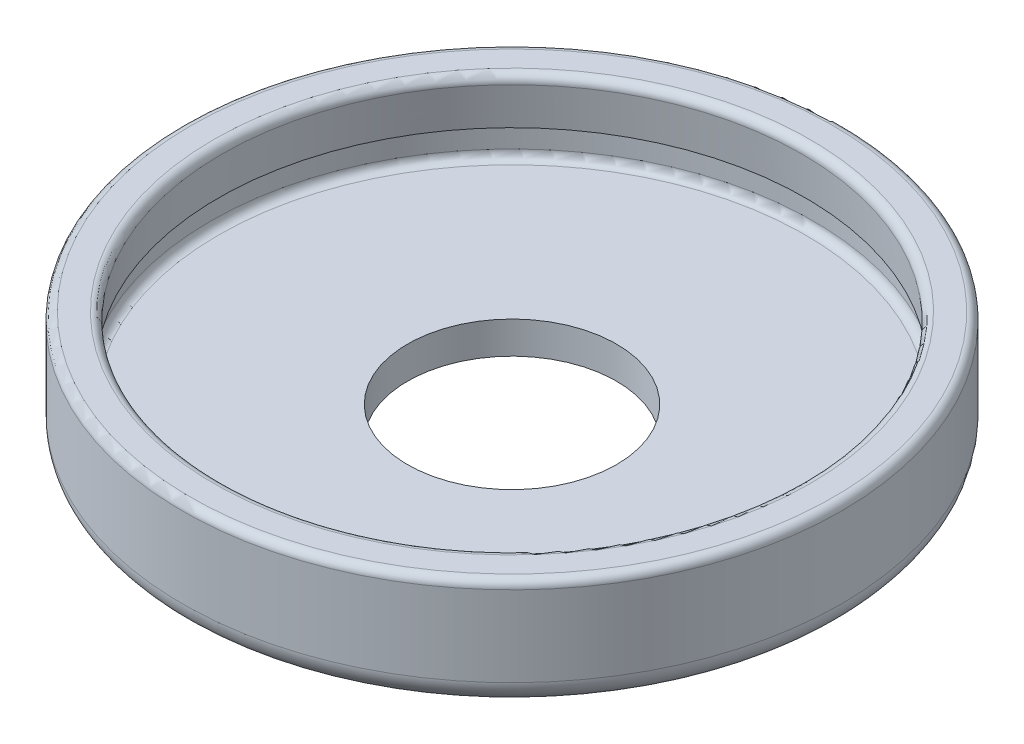
SolidWorks part; units mm, degrees
ref_plane "Front Plane" through (0, 0, 0) normal (0, 0, 1) x (1, 0, 0)
ref_plane "Top Plane" through (0, 0, 0) normal (0, 1, 0) x (1, 0, 0)
ref_plane "Right Plane" through (0, 0, 0) normal (1, 0, 0) x (0, 0, -1)
sketch "Sketch1" plane through (0, 0, 0) normal (0, 0, 1) x (1, 0, 0)
  line L0 (-1.5505, 0) -> (75.9722, 0) construction
  line L1 (0, -1.5505) -> (0, 75.9722) construction
  line L2 (5.207, 1.778) -> (5.207, 0)
  line L3 (5.207, 0) -> (1.651, 0)
  line L4 (5.207, 1.778) -> (4.572, 1.778)
  line L6 (4.6355, 1.016) -> (4.7625, 1.016)
  line L7 (4.7625, 1.016) -> (4.7625, 0.508)
  line L8 (4.7625, 0.508) -> (1.651, 0.508)
  line L9 (1.651, 0.508) -> (1.651, 0)
  line L10 (4.6355, 1.016) -> (4.7625, 1.016)
  line L11 (4.572, 1.778) -> (4.6355, 1.016)
  dimension "D1" = 3.302
  dimension "D2" = 10.414
  dimension "D3" = 1.778
  dimension "D4" = 0.635
  dimension "D5" = 0.762
  dimension "D6" = 0.508
  dimension "D7" = 9.271
  dimension "D8" = 9.525
revolve "Revolve1" add sketch "Sketch1" angle 360 about L1
fillet "Fillet1" radius 0.381 1 edges at (5.207, 0, 0)
fillet "Fillet2" radius 0.127 3 edges at (4.7625, 0.508, 0) (5.207, 1.778, 0) (4.572, 1.778, 0)
